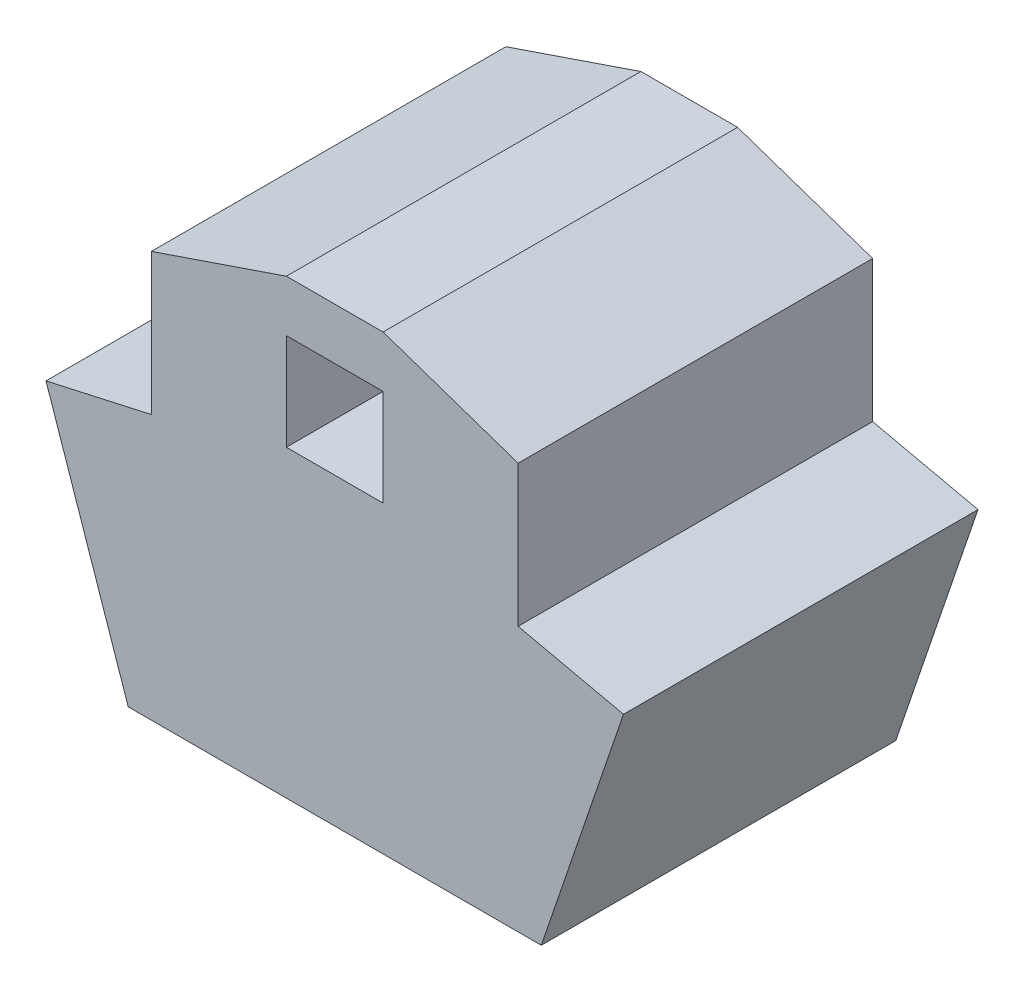
SolidWorks part; units mm, degrees
ref_plane "Front Plane" through (0, 0, 0) normal (0, 0, 1) x (1, 0, 0)
ref_plane "Top Plane" through (0, 0, 0) normal (0, 1, 0) x (1, 0, 0)
ref_plane "Right Plane" through (0, 0, 0) normal (1, 0, 0) x (0, 0, -1)
sketch "Sketch1" plane through (0, 0, 0) normal (0, 0, 1) x (1, 0, 0)
  line L0 (0, 45.5072) -> (0, -40.4348) construction
  line L1 (-48.8406, 0) -> (45.7971, 0) construction
  line L3 (10.0225, -10.0225) -> (-10.0225, -10.0225)
  line L4 (10.0225, -10.0225) -> (10.0225, 10.0225)
  line L5 (10.0225, 10.0225) -> (-10.0225, 10.0225)
  line L6 (-10.0225, -10.0225) -> (-10.0225, 10.0225)
  line L7 (10.0225, -10.0225) -> (-10.0225, 10.0225) construction
  line L8 (10.0225, 10.0225) -> (-10.0225, -10.0225) construction
  line L18 (-12.5, -26.0225) -> (12.5, -26.0225)
  line L19 (12.5, -26.0225) -> (20, -48.0225)
  line L20 (-20, -48.0225) -> (20, -48.0225)
  line L21 (-12.5, -26.0225) -> (-20, -48.0225)
  line L40 (15.6695, -26.0225) -> (23.1695, -48.0225)
  line L45 (15.6695, -26.0225) -> (55.6695, -26.0225)
  line L47 (55.6695, -26.0225) -> (48.1695, -48.0225)
  line L49 (48.1695, -48.0225) -> (23.1695, -48.0225)
  line L51 (59.8618, -23.0225) -> (50.3163, -51.0225)
  line L53 (-35.6695, -48.0225) -> (-35.6695, -55.9008) construction
  line L54 (15.6695, -23.0225) -> (59.8618, -23.0225) construction
  line L55 (-15.6695, -26.0225) -> (-55.6695, -26.0225)
  line L56 (14.6468, -23.0225) -> (24.1923, -51.0225) construction
  line L57 (-24.1923, -51.0225) -> (24.1923, -51.0225) construction
  line L58 (50.3163, -51.0225) -> (23.1695, -51.0225) construction
  line L59 (-55.6695, -26.0225) -> (-48.1695, -48.0225)
  line L60 (-48.1695, -48.0225) -> (-23.1695, -48.0225)
  line L61 (-15.6695, -26.0225) -> (-23.1695, -48.0225)
  line L62 (-14.6468, -23.0225) -> (-24.1923, -51.0225) construction
  line L64 (-59.8618, -23.0225) -> (-50.3163, -51.0225)
  line L67 (-11.4773, -23.0225) -> (-21.0227, -51.0225) construction
  line L68 (-11.4773, -23.0225) -> (-59.8618, -23.0225) construction
  line L69 (-14.6468, -23.0225) -> (14.6468, -23.0225) construction
  line L70 (-50.3163, -51.0225) -> (-21.0227, -51.0225) construction
  line L71 (-50.3163, -51.0225) -> (50.3163, -51.0225)
  line L72 (-13.0225, -23.5) -> (-13.0225, 16.5)
  line L73 (-13.0225, 16.5) -> (-35.0225, 9)
  line L74 (-35.0225, 9) -> (-35.0225, -16)
  line L75 (-35.0225, -16) -> (-13.0225, -23.5)
  line L76 (-39.4516, -3.5) -> (45.7971, -3.5) construction
  line L77 (35.0225, 9) -> (35.0225, -16)
  line L78 (13.0225, 16.5) -> (35.0225, 9)
  line L79 (13.0225, -23.5) -> (13.0225, 16.5)
  line L80 (35.0225, -16) -> (13.0225, -23.5)
  line L83 (-10.0225, 20.6923) -> (-38.0225, 11.1468)
  line L84 (-38.0225, 11.1468) -> (-38.0225, -18.1468)
  line L85 (-10.0225, -27.6923) -> (-10.0225, 20.6923) construction
  line L86 (-38.0225, -18.1468) -> (-10.0225, -27.6923) construction
  line L87 (-59.8618, -23.0225) -> (-38.0225, -18.1468)
  line L88 (-10.0225, 20.6923) -> (0, 20.6923)
  line L89 (38.0225, 11.1468) -> (38.0225, -18.1468)
  line L92 (10.0225, 20.6923) -> (38.0225, 11.1468)
  line L93 (10.0225, -27.6923) -> (10.0225, 20.6923) construction
  line L94 (38.0225, -18.1468) -> (10.0225, -27.6923) construction
  line L95 (59.8618, -23.0225) -> (38.0225, -18.1468)
  line L96 (10.0225, 20.6923) -> (0, 20.6923)
  point P5 (0, 0)
  point P10 (0, 0)
  point P13 (0, 14)
  point P14 (0, 35)
  point P16 (22.4772, 38)
  point P18 (-22.4772, 38)
  point P19 (0, 35)
  point P20 (-14.7629, 11)
  point P33 (14.7629, 11)
  dimension "D1" = 20.045
  dimension "D2" = 20.045
  dimension "D3" = 25
  dimension "D4" = 40
  dimension "D5" = 22
  dimension "D6" = 3
  dimension "D8" = 16
  dimension "D9" = 20
  dimension "D10" = 3
  dimension "D11" = 40
  dimension "D7" = 12.5
  dimension "D13" = 3
  dimension "D14" = 40
  dimension "D15" = 25
  dimension "D16" = 3.5
  dimension "D17" = 12.5
  dimension "D18" = 20
  dimension "D19" = 22
  dimension "D12" = 3
  dimension "D20" = 3
  dimension "D21" = 3
extrude "Boss-Extrude1" add sketch "Sketch1" along normal blind 73.5
sketch "Sketch2" plane through (0, 0, 0) normal (0, 0, 1) x (1, 0, 0)
  line L5 (0, 26.7053) -> (0, -60.761) construction
  line L16 (-15.6695, -24.0225) -> (-55.6695, -24.0225)
  line L17 (-17.688, -24.0225) -> (-55.162, -24.0225)
  line L19 (-37.5867, -20.0988) -> (-59.426, -24.9744)
  line L20 (-32.5174, -18.967) -> (-55.162, -24.0225)
  line L21 (17.688, -24.0225) -> (55.162, -24.0225)
  line L22 (-35.6678, -17.893) -> (-13.6678, -25.393)
  line L23 (-32.5174, -18.967) -> (-17.688, -24.0225)
  line L24 (32.5174, -18.967) -> (55.162, -24.0225)
  line L25 (32.5174, -18.967) -> (17.688, -24.0225)
  dimension "D1" = 2
  dimension "D2" = 2
  dimension "D3" = 2
extrude "Cut-Extrude2" cut sketch "Sketch2" along normal through all
sketch "Sketch3" plane through (0, 0, 0) normal (0, 0, 1) x (1, 0, 0)
  line L0 (0, 24.4574) -> (0, -32.3369) construction
  ellipse E0 centre (0, -18) end of major axis (9, -18) minor radius 5
  dimension "D1" = 18
  dimension "D2" = 9
  dimension "D5" = 5
extrude "Cut-Extrude4" cut sketch "Sketch3" along normal through all
sketch "Sketch4" plane through (0, 0, 0) normal (1, 0, 0) x (0, 0, -1)
  line L0 (-89.3161, -36.52) -> (42.3095, -36.52) construction
  line L1 (-36.75, 29.8449) -> (-36.75, -56.0115) construction
  line L2 (-36.75, -36.52) -> (-58.75, -36.52) construction
  line L3 (-36.75, -36.52) -> (-14.75, -36.52) construction
  line L4 (-36.75, -36.52) -> (-14.75, -36.52) construction
  circle A0 centre (-36.75, -36.52) radius 7
  circle A2 centre (-58.75, -36.52) radius 7
  circle A3 centre (-14.75, -36.52) radius 7
  dimension "D3" = 14
  dimension "D1" = 36.52
  dimension "D2" = 36.75
  dimension "D5" = 22
  dimension "D7" = 22
  dimension "D6" = 2
  dimension "D4" = 2
extrude "Cut-Extrude5" cut sketch "Sketch4" against normal through all both and the other way through all
sketch "Sketch5" plane through (38.0225, 0, 0) normal (1, 0, 0) x (0, 0, -1)
  line L0 (-85.8813, -3.5) -> (19.6328, -3.5) construction
  line L1 (-36.75, -3.5) -> (-14.75, -3.5) construction
  line L2 (-36.75, -3.5) -> (-58.75, -3.5) construction
  circle A0 centre (-36.75, -3.5) radius 7
  circle A1 centre (-14.75, -3.5) radius 7
  circle A2 centre (-58.75, -3.5) radius 7
  dimension "D2" = 14
  dimension "D3" = 36.75
  dimension "D1" = 3.5
  dimension "D5" = 22
  dimension "D7" = 22
  dimension "D4" = 2
  dimension "D6" = 2
extrude "Cut-Extrude6" cut sketch "Sketch5" against normal blind 10
sketch "Sketch6" plane through (-38.0225, 0, 0) normal (-1, 0, 0) x (0, 0, 1)
  line L0 (-12.5672, -3.5) -> (85.8413, -3.5) construction
  line L1 (36.75, -3.5) -> (58.75, -3.5) construction
  line L2 (36.75, -3.5) -> (14.75, -3.5) construction
  circle A0 centre (36.75, -3.5) radius 7
  circle A1 centre (58.75, -3.5) radius 7
  circle A2 centre (14.75, -3.5) radius 7
  dimension "D2" = 14
  dimension "D3" = 36.75
  dimension "D1" = 3.5
  dimension "D5" = 22
  dimension "D7" = 22
  dimension "D4" = 2
  dimension "D6" = 2
extrude "Cut-Extrude7" cut sketch "Sketch6" against normal blind 10
sketch "Sketch7" plane through (0, -51.0225, 0) normal (0, -1, 0) x (1, 0, 0)
  line L0 (0, 77.452) -> (0, -13.4565) construction
  line L1 (0, 36.75) -> (35.16, 36.75) construction
  line L2 (0, 36.75) -> (-35.16, 36.75) construction
  circle A0 centre (0, 36.75) radius 7.5
  circle A1 centre (35.16, 36.75) radius 7.5
  circle A4 centre (-35.16, 36.75) radius 7.5
  circle A5 centre (0, 58.75) radius 7.5 [skipped]
  circle A6 centre (35.16, 58.75) radius 7.5 [skipped]
  circle A7 centre (0, 58.75) radius 7.5
  circle A8 centre (35.16, 58.75) radius 7.5
  circle A9 centre (-35.16, 58.75) radius 7.5
  circle A10 centre (0, 14.75) radius 7.5
  circle A11 centre (35.16, 14.75) radius 7.5
  circle A12 centre (-35.16, 14.75) radius 7.5
  dimension "D1" = 15
  dimension "D2" = 36.75
  dimension "D5" = 35.16
  dimension "D7" = 35.16
  dimension "D3" = 2
  dimension "D4" = 2
  dimension "D6" = 2
  dimension "D8" = 2
  dimension "D9" = 2
extrude "Cut-Extrude8" cut sketch "Sketch7" against normal blind 10
sketch "Sketch8" plane through (0, 0, 0) normal (0, 1, 0) x (1, 0, 0)
  line L0 (0, 9.1455) -> (0, -79.6194) construction
  circle A0 centre (23.52, -36.75) radius 7
  circle A1 centre (23.52, -14.75) radius 7
  circle A2 centre (23.52, -58.75) radius 7
  circle A3 centre (-23.52, -58.75) radius 7
  circle A4 centre (-23.52, -14.75) radius 7
  circle A5 centre (-23.52, -36.75) radius 7
  dimension "D1" = 14
  dimension "D2" = 36.75
  dimension "D3" = 23.52
  dimension "D4" = 2
  dimension "D5" = 2
extrude "Cut-Extrude9" cut sketch "Sketch8" along normal through all and the other way up to surface other way up to face at (-36.425, -24.0225, 36.75)
sketch "Sketch9" plane through (0, 20.6923, 0) normal (0, 1, 0) x (1, 0, 0)
  line L0 (0, 10.7424) -> (0, -82.6878) construction
  line L1 (-69.9781, -36.75) -> (68.9694, -36.75) construction
  circle A0 centre (0, -10) radius 2.75
  circle A1 centre (0, -63.5) radius 2.75
  point P5 (0, -10)
  dimension "D2" = 5.5
  dimension "D1" = 36.75
  dimension "D4" = 26.75
extrude "Cut-Extrude10" cut sketch "Sketch9" against normal blind 15
sketch "Sketch10" plane through (0, 20.6923, 0) normal (0, 1, 0) x (1, 0, 0)
  circle A0 centre (0, -10) radius 5.1
  circle A1 centre (0, -63.5) radius 5.1
  dimension "D1" = 10.2
  dimension "D2" = 10.2
extrude "Cut-Extrude11" cut sketch "Sketch10" against normal blind 4
sketch "Sketch11" plane through (0, 0, 0) normal (0, 0, 1) x (1, 0, 0)
  line L0 (0, 36.7796) -> (0, -82.5434) construction
  line L1 (-50.3163, -51.0225) -> (-42.8163, -73.0225)
  line L2 (-42.8163, -73.0225) -> (42.8163, -73.0225)
  line L3 (-59.8618, -23.0225) -> (-50.3163, -51.0225) construction
  line L4 (-50.3163, -51.0225) -> (50.3163, -51.0225) construction
  line L5 (50.3163, -51.0225) -> (42.8163, -73.0225)
  line L6 (-10.0225, -10.0225) -> (10.0225, -10.0225) construction
  line L7 (10.0225, -10.0225) -> (10.0225, 10.0225) construction
  line L8 (10.0225, 10.0225) -> (-10.0225, 10.0225) construction
  line L9 (-10.0225, 10.0225) -> (-10.0225, -10.0225) construction
  line L10 (-10.0225, -10.0225) -> (10.0225, -10.0225)
  line L11 (10.0225, -10.0225) -> (10.0225, 10.0225)
  line L12 (10.0225, 10.0225) -> (-10.0225, 10.0225)
  line L13 (-10.0225, 10.0225) -> (-10.0225, -10.0225)
  line L15 (59.8618, -23.0225) -> (38.0225, -18.1468)
  line L16 (38.0225, -18.1468) -> (38.0225, 11.1468)
  line L17 (38.0225, 11.1468) -> (10.0225, 20.6923)
  line L18 (10.0225, 20.6923) -> (-10.0225, 20.6923)
  line L19 (-10.0225, 20.6923) -> (-38.0225, 11.1468)
  line L20 (-38.0225, 11.1468) -> (-38.0225, -18.1468)
  line L21 (-38.0225, -18.1468) -> (-59.8618, -23.0225)
  line L22 (-59.8618, -23.0225) -> (-50.3163, -51.0225)
  line L23 (-50.3163, -51.0225) -> (50.3163, -51.0225)
  line L24 (50.3163, -51.0225) -> (59.8618, -23.0225)
  line L25 (59.8618, -23.0225) -> (38.0225, -18.1468)
  line L26 (38.0225, -18.1468) -> (38.0225, 11.1468)
  line L27 (38.0225, 11.1468) -> (10.0225, 20.6923)
  line L28 (10.0225, 20.6923) -> (-10.0225, 20.6923)
  line L29 (-10.0225, 20.6923) -> (-38.0225, 11.1468)
  line L30 (-38.0225, 11.1468) -> (-38.0225, -18.1468)
  line L31 (-38.0225, -18.1468) -> (-59.8618, -23.0225)
  line L32 (-59.8618, -23.0225) -> (-50.3163, -51.0225)
  line L34 (50.3163, -51.0225) -> (59.8618, -23.0225)
  point P15 (0, -73.0225)
  dimension "D1" = 22
  dimension "D2" = 0
extrude "Boss-Extrude2" add sketch "Sketch11" along normal up to surface (73.5 mm away) up to face at (9, -18, 73.5)
